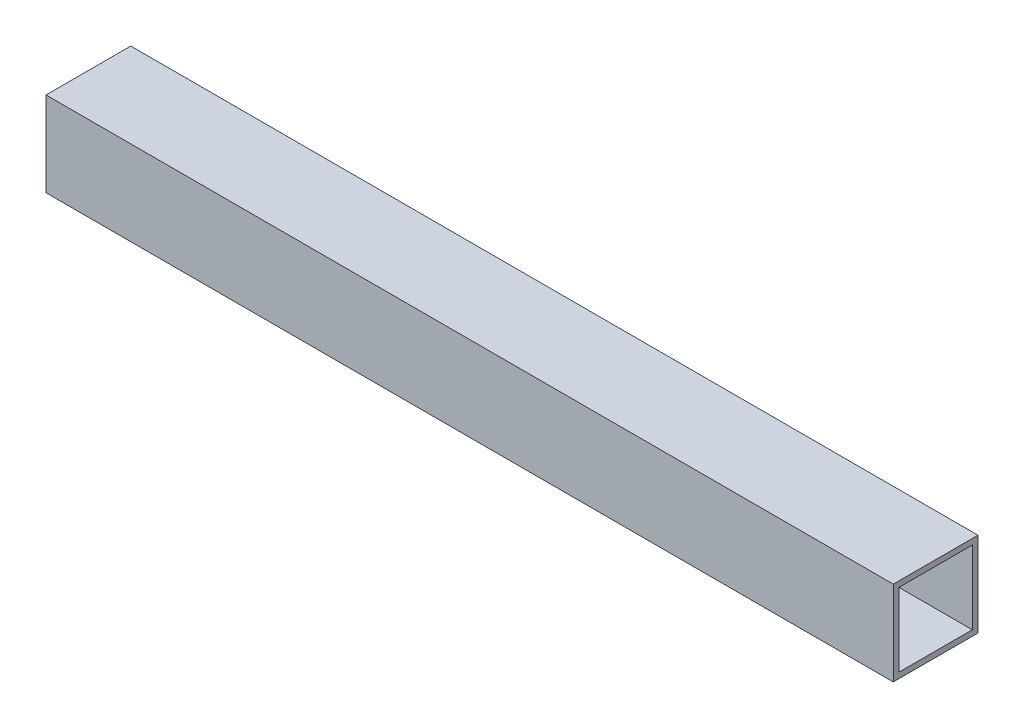
SolidWorks part; units mm, degrees
material "Thornel Mat VMA"
ref_plane "前视基准面" through (0, 0, 0) normal (0, 0, 1) x (1, 0, 0)
ref_plane "上视基准面" through (0, 0, 0) normal (0, 1, 0) x (1, 0, 0)
ref_plane "右视基准面" through (0, 0, 0) normal (1, 0, 0) x (0, 0, -1)
sketch "草图1" plane through (0, 0, 0) normal (1, 0, 0) x (0, 0, -1)
  line L1 (7.5, 7.5) -> (-7.5, 7.5)
  line L2 (7.5, 7.5) -> (7.5, -7.5)
  line L3 (7.5, -7.5) -> (-7.5, -7.5)
  line L4 (-7.5, 7.5) -> (-7.5, -7.5)
  line L5 (7.5, 7.5) -> (-7.5, -7.5) construction
  line L6 (7.5, -7.5) -> (-7.5, 7.5) construction
  line L7 (6.5, 6.5) -> (-6.5, 6.5)
  line L8 (6.5, 6.5) -> (6.5, -6.5)
  line L9 (6.5, -6.5) -> (-6.5, -6.5)
  line L10 (-6.5, 6.5) -> (-6.5, -6.5)
  line L11 (6.5, 6.5) -> (-6.5, -6.5) construction
  line L12 (6.5, -6.5) -> (-6.5, 6.5) construction
  point P0 (0, 0)
  point P6 (0, 0)
  dimension "D1" = 15
  dimension "D2" = 1
extrude "凸台-拉伸1" add sketch "草图1" along normal mid plane 150
